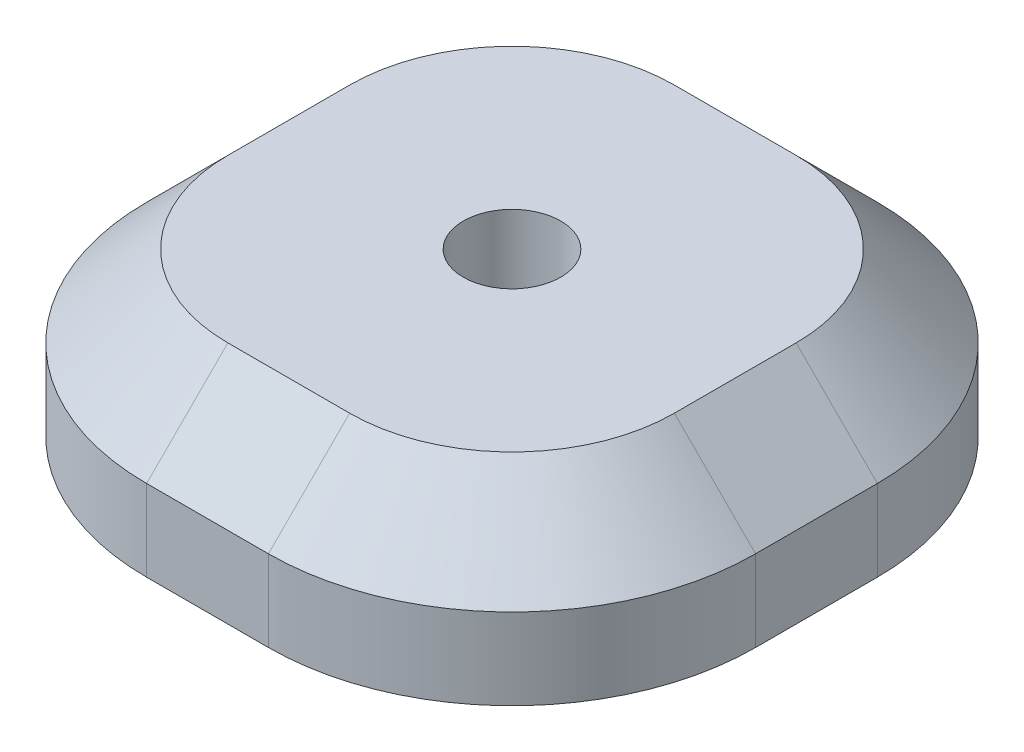
SolidWorks part; units mm, degrees
ref_plane "Front Plane" through (0, 0, 0) normal (0, 0, 1) x (1, 0, 0)
ref_plane "Top Plane" through (0, 0, 0) normal (0, 1, 0) x (1, 0, 0)
ref_plane "Right Plane" through (0, 0, 0) normal (1, 0, 0) x (0, 0, -1)
sketch "Sketch1" plane through (0, 0, 0) normal (0, 1, 0) x (1, 0, 0)
  line L0 (-7.5, 37.5) -> (7.5, 37.5)
  line L1 (37.5, 7.5) -> (37.5, -7.5)
  line L2 (7.5, -37.5) -> (-7.5, -37.5)
  line L3 (-37.5, -7.5) -> (-37.5, 7.5)
  arc A0 (-7.5, -37.5) -> (-37.5, -7.5) centre (-7.5, -7.5) cw
  arc A1 (37.5, -7.5) -> (7.5, -37.5) centre (7.5, -7.5) cw
  arc A2 (7.5, 37.5) -> (37.5, 7.5) centre (7.5, 7.5) cw
  arc A3 (-7.5, 37.5) -> (-37.5, 7.5) centre (-7.5, 7.5) ccw
  point P4 (0, 37.5)
  point P5 (-37.5, 0)
  point P13 (37.5, 37.5)
  point P16 (-37.5, 37.5)
  dimension "D2" = 30
  dimension "D1" = 75
extrude "Boss-Extrude1" add sketch "Sketch1" along normal mid plane 20
chamfer "Chamfer1" distance 10 angle 45 8 edges at (-37.5, 10, 0) (-28.7132, 10, -28.7132) (0, 10, -37.5) (28.7132, 10, -28.7132) (37.5, 10, 0) (28.7132, 10, 28.7132) (0, 10, 37.5) (-28.7132, 10, 28.7132)
sketch "Sketch3" plane through (0, -10, 0) normal (0, -1, 0) x (1, 0, 0)
  line L0 (12.5, 37.5) -> (12.5, -37.5) construction
  line L1 (-7.5, 37.5) -> (7.5, 37.5) construction
  line L2 (7.5, -37.5) -> (-7.5, -37.5) construction
  line L3 (-37.5, 12.5) -> (37.5, 12.5) construction
  line L4 (-37.5, -7.5) -> (-37.5, 7.5) construction
  line L5 (37.5, 7.5) -> (37.5, -7.5) construction
  line L6 (0, 37.5) -> (0, -37.5) construction
  line L7 (-37.5, 0) -> (37.5, 0) construction
  circle A0 centre (12.5, 12.5) radius 6
  circle A1 centre (-12.5, 12.5) radius 6
  circle A2 centre (12.5, -12.5) radius 6
  circle A3 centre (-12.5, -12.5) radius 6
  dimension "D1" = 25
  dimension "D2" = 25
extrude "Cut-Extrude2" cut sketch "Sketch3" against normal offset from surface (10 mm away) 10 up to face at (0, -10, 0)
sketch "Sketch5" plane through (0, 10, 0) normal (0, 1, 0) x (1, 0, 0)
  circle A0 centre (0, 0) radius 6
extrude "Cut-Extrude3" cut sketch "Sketch5" against normal offset from surface (10 mm away) 10 up to face at (0, 10, 0)
